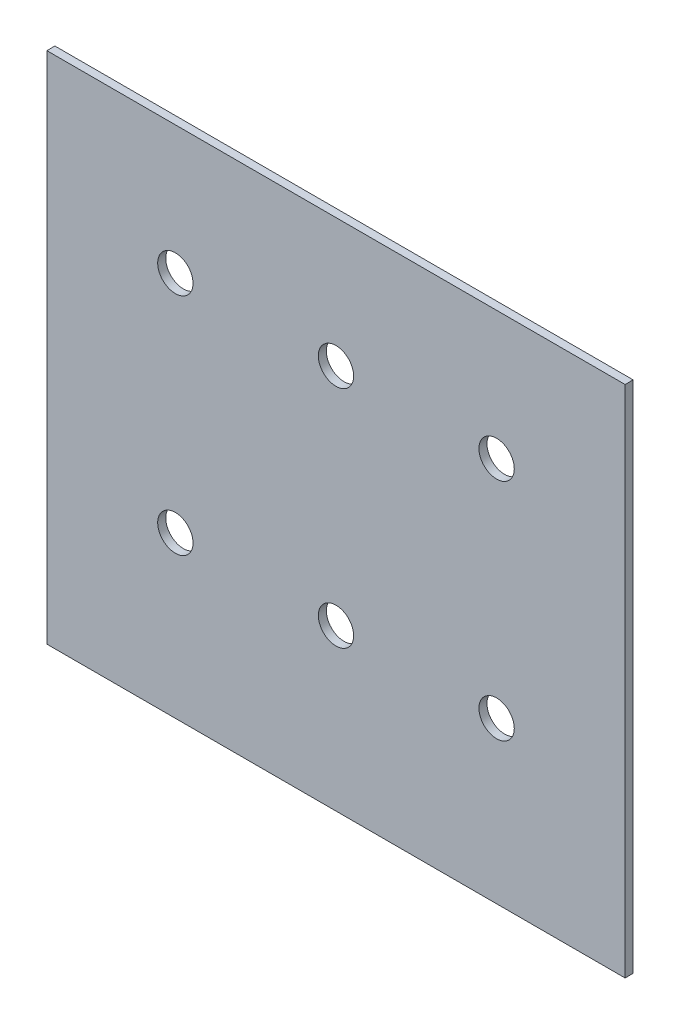
SolidWorks part; units mm, degrees
ref_plane "Plano frontal" through (0, 0, 0) normal (0, 0, 1) x (1, 0, 0)
ref_plane "Plano superior" through (0, 0, 0) normal (0, 1, 0) x (1, 0, 0)
ref_plane "Plano direito" through (0, 0, 0) normal (1, 0, 0) x (0, 0, -1)
sketch "Esboço1" plane through (0, 0, 0) normal (0, 0, 1) x (1, 0, 0)
  line L0 (0, 110) -> (0, -110) construction
  line L1 (-180, 160) -> (180, 160)
  line L2 (-180, 160) -> (-180, -160)
  line L3 (-180, -160) -> (180, -160)
  line L4 (180, 160) -> (180, -160)
  line L5 (-180, 160) -> (180, -160) construction
  line L6 (-180, -160) -> (180, 160) construction
  line L7 (-130, -110) -> (130, -110) construction
  line L8 (-130, -110) -> (-130, 110) construction
  line L9 (-130, 110) -> (130, 110) construction
  line L10 (130, -110) -> (130, 110) construction
  line L11 (-130, -110) -> (130, 110) construction
  line L12 (-130, 110) -> (130, -110) construction
  line L13 (180, 80) -> (-180, 80) construction
  line L14 (180, -60) -> (-180, -60) construction
  line L15 (-100, 160) -> (-100, -160) construction
  line L16 (100, 160) -> (100, -160) construction
  circle A0 centre (0, 80) radius 11
  circle A1 centre (-100, 80) radius 11
  circle A2 centre (100, 80) radius 11
  circle A3 centre (0, -60) radius 11
  circle A4 centre (100, -60) radius 11
  circle A5 centre (-100, -60) radius 11
  point P0 (0, 0)
  point P6 (0, 0)
  point P33 (0, 0)
  point P34 (0, 0)
  point P35 (0, 0)
  point P36 (0, 0)
  dimension "D5" = 22
  dimension "D1" = 360
  dimension "D2" = 320
  dimension "D3" = 260
  dimension "D4" = 220
  dimension "D6" = 30
  dimension "D8" = 100
  dimension "D9" = 100
  dimension "D7" = 140
extrude "Ressalto-extrusão1" add sketch "Esboço1" along normal blind 5
